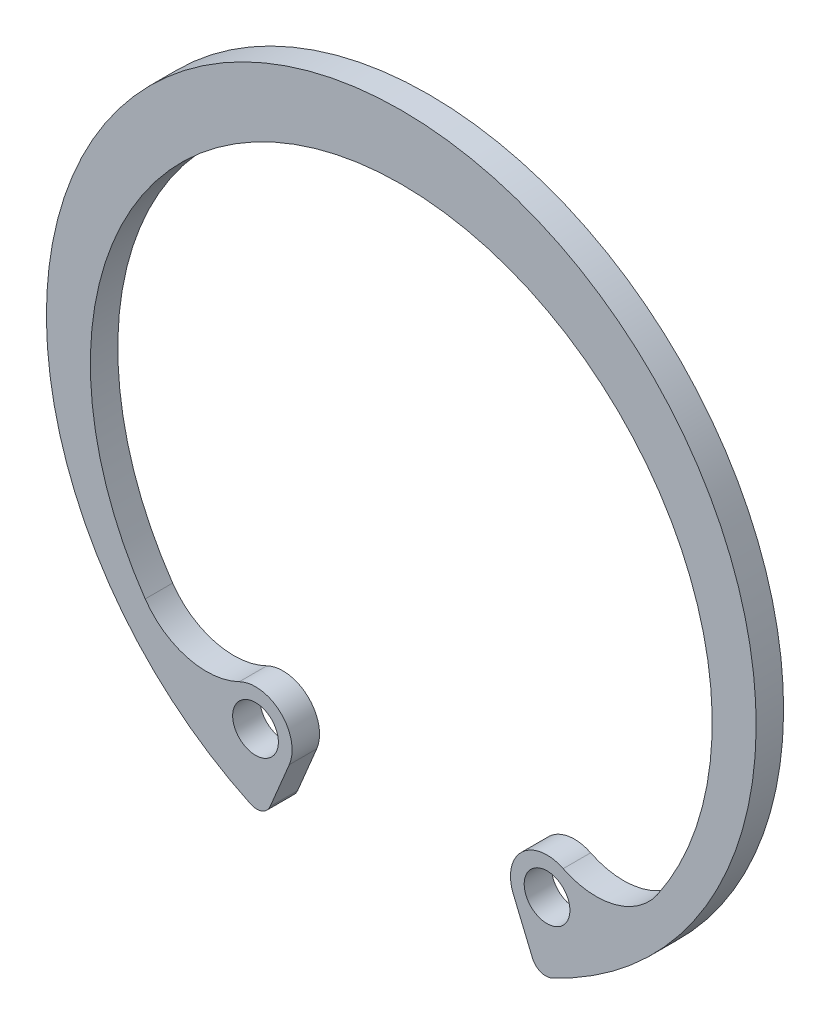
SolidWorks part; units mm, degrees
ref_plane "Front Plane" through (0, 0, 0) normal (0, 0, 1) x (1, 0, 0)
ref_plane "Top Plane" through (0, 0, 0) normal (0, 1, 0) x (1, 0, 0)
ref_plane "Right Plane" through (0, 0, 0) normal (1, 0, 0) x (0, 0, -1)
sketch "Sketch1" plane through (0, 0, 0) normal (0, 0, 1) x (1, 0, 0)
  line L0 (0, 19.4) -> (0, 15.9) construction
  line L1 (-19.4, 0) -> (-17.65, 0) construction
  line L2 (0, 0) -> (0, -19.4) construction
  line L3 (-5.4, -12.9167) -> (-7.4829, -17.8988) construction
  line L4 (-5.4, -12.9167) -> (-7.9, -12.9167) construction
  circle A0 centre (0, 0) radius 19 construction
  circle A1 centre (0, 0) radius 19.4 construction
  circle A2 centre (0, 0) radius 18 construction
  dimension "Ring OD" = 38.8
  dimension "For ID" = 36
  dimension "Maximum Section" = 3.5
  dimension "Minimum Section" = 1.75
  dimension "Gap Width" = 10.8
  dimension "Lug Height" = 5.4
  dimension "Hole Diameter" = 2.5
sketch "Sketch2" plane through (0, 0, 0) normal (1, 0, 0) x (0, 0, -1)
  line L0 (-0.8, 19.4) -> (0.8, 19.4) construction
  line L1 (-0.75, -19.4) -> (0.75, -19.4) construction
  point P3 (0, 19.4)
  point P7 (0, -19.4)
  point P8 (-0.75, -19.4)
  point P10 (0.75, -19.4)
  point P11 (-0.8, 19.4)
  point P12 (0.8, 19.4)
  dimension "For Groove Width" = 1.6
  dimension "Ring Thickness" = 1.5
sketch "Sketch3" plane through (0, 0, 0) normal (0, 0, 1) x (1, 0, 0)
  line L0 (-7.4829, -17.8988) -> (-5.4427, -13.0188) construction
  line L1 (-5.4427, -13.0188) -> (-8.3259, -11.363) construction
  line L2 (0, 0) -> (-6.9722, -12.1403) construction
  line L3 (-13.9998, -10.737) -> (0, 0) construction
  line L4 (0, 0) -> (0, -19.4) construction
  line L5 (-8.3259, -11.363) -> (0, 0) construction
  line L6 (-6.9722, -12.1403) -> (-7.9683, -13.8747) construction
  line L7 (-7.9683, -13.8747) -> (-8.9643, -15.609) construction
  line L8 (0, 19.4) -> (0, 15.9) construction
  line L11 (-6.123, -14.6461) -> (-7.4829, -17.8988)
  line L12 (0, 0) -> (0, -19.4) construction
  line L13 (6.123, -14.6461) -> (7.4829, -17.8988)
  line L14 (-5.4, -12.9167) -> (-7.4829, -17.8988) construction
  line L15 (-6.9722, -12.1403) -> (-9.6615, -16.8231) construction
  arc A0 (-7.4829, -17.8988) -> (7.4829, -17.8988) centre (0, 0) cw
  circle A1 centre (0, 0) radius 19.4 construction
  arc A2 (-13.9998, -10.737) -> (13.9998, -10.737) centre (0, -1.0975) cw
  circle A4 centre (-7.9683, -13.8747) radius 1.25
  circle A5 centre (0, 0) radius 17.65 construction
  circle A7 centre (7.9683, -13.8747) radius 1.25
  circle A8 centre (0, 0) radius 18 construction
  arc A9 (-8.8514, -12.0802) -> (-6.123, -14.6461) centre (-7.9683, -13.8747) cw
  arc A10 (-13.9998, -10.737) -> (-8.8514, -12.0802) centre (-10.6483, -8.4294) ccw
  arc A11 (8.8514, -12.0802) -> (6.123, -14.6461) centre (7.9683, -13.8747) ccw
  arc A12 (13.9998, -10.737) -> (8.8514, -12.0802) centre (10.6483, -8.4294) cw
  point P3 (0, -19.4)
  dimension "D1" = 2.5
  dimension "D2" = 5.4
  dimension "D3" = 8.775
extrude "Boss-Extrude1" add sketch "Sketch3" against normal up to vertex (0.75 mm away) and the other way up to vertex (0.75 mm away) up to point (0, -19.4, -0.75) other way up to point (0, -19.4, 0.75)
fillet "Fillet1" radius 0.7937 2 edges at (7.4829, -17.8988, 0) (-7.4829, -17.8988, 0)
equation "\"D1@Sketch3\"=\"Hole Diameter@Sketch1\""
equation "\"Minimum Section@Sketch1\"=\"Maximum Section@Sketch1\"*.5"
equation "\"Gap Width@Sketch1\"=\"For ID@Sketch1\"*.3"
equation "\"D2@Sketch3\"=\"Lug Height@Sketch1\""
equation "\"D3@Sketch3\"=\"Lug Height@Sketch1\"*1.625"
